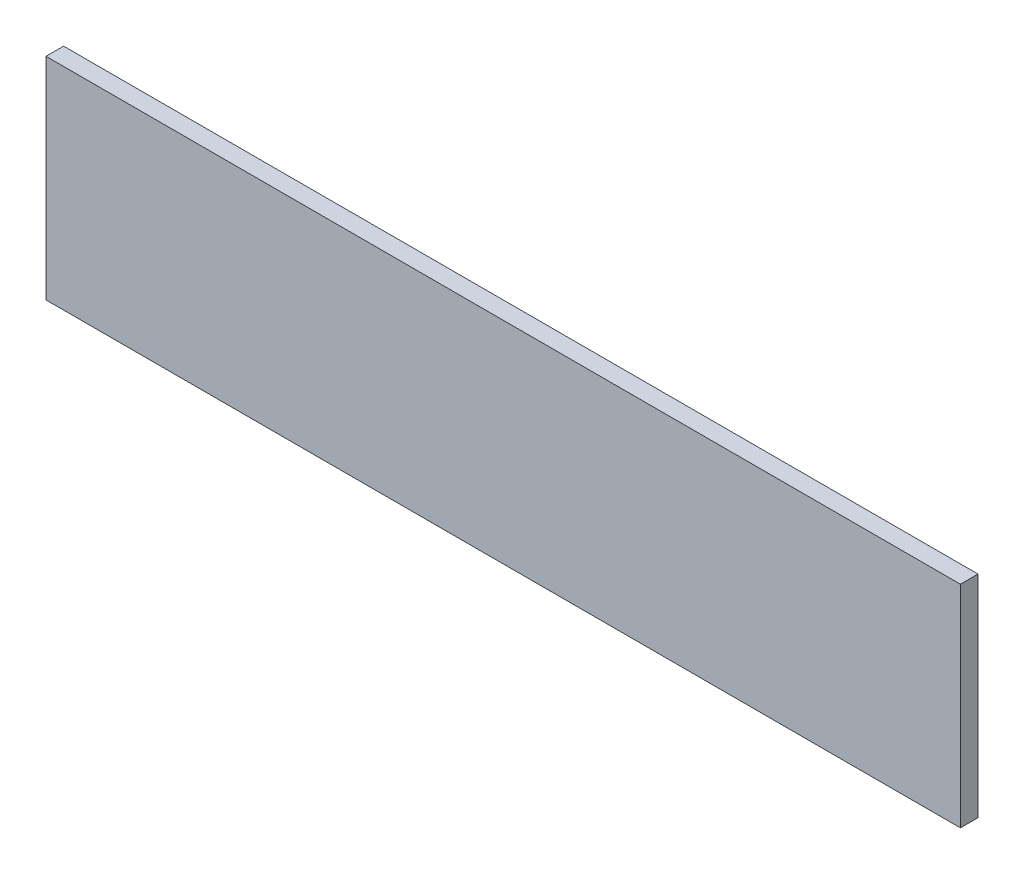
SolidWorks part; units mm, degrees
ref_plane "Front" through (0, 0, 0) normal (0, 0, 1) x (1, 0, 0)
ref_plane "Top" through (0, 0, 0) normal (0, 1, 0) x (1, 0, 0)
ref_plane "Right" through (0, 0, 0) normal (1, 0, 0) x (0, 0, -1)
sketch "Sketch1" plane through (0, 0, 0) normal (0, 0, 1) x (1, 0, 0)
  line L1 (0, 0) -> (330.2, 0)
  line L2 (0, 0) -> (0, 76.2)
  line L3 (0, 76.2) -> (330.2, 76.2)
  line L4 (330.2, 0) -> (330.2, 76.2)
  dimension "D1" = 76.2
  dimension "D2" = 330.2
extrude "Boss-Extrude1" add sketch "Sketch1" along normal blind 6.35
